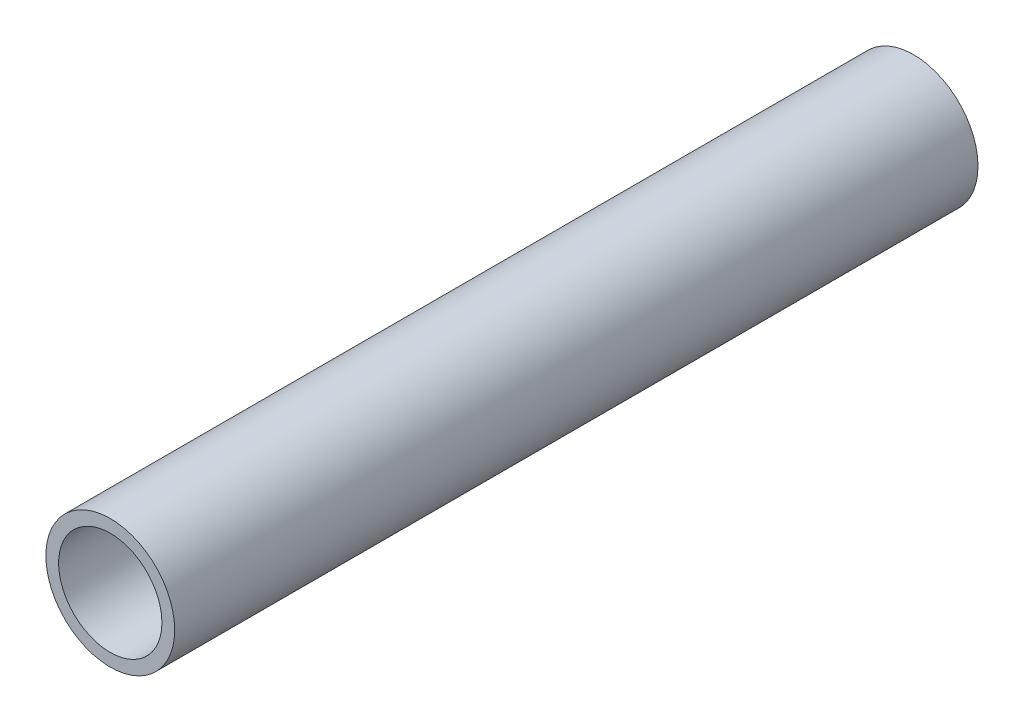
SolidWorks part; units mm, degrees
ref_plane "Front Plane" through (0, 0, 0) normal (0, 0, 1) x (1, 0, 0)
ref_plane "Top Plane" through (0, 0, 0) normal (0, 1, 0) x (1, 0, 0)
ref_plane "Right Plane" through (0, 0, 0) normal (1, 0, 0) x (0, 0, -1)
sketch "Sketch1" plane through (0, 0, 0) normal (0, 0, 1) x (1, 0, 0)
  circle A0 centre (0, 0) radius 4.05
  dimension "D1" = 8.1
extrude "Extrude-Thin1" add sketch "Sketch1" along normal blind 63 thin
